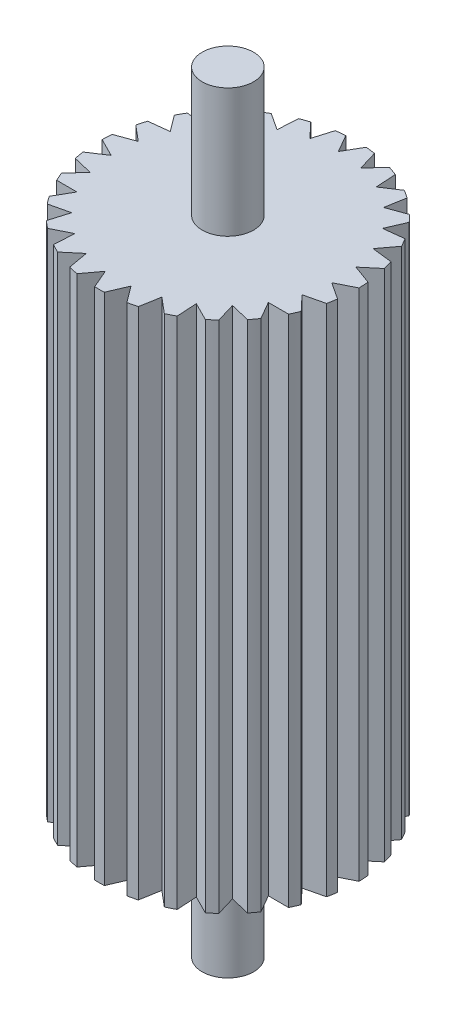
SolidWorks part; units mm, degrees
ref_plane "Front Plane" through (0, 0, 0) normal (0, 0, 1) x (1, 0, 0)
ref_plane "Top Plane" through (0, 0, 0) normal (0, 1, 0) x (1, 0, 0)
ref_plane "Right Plane" through (0, 0, 0) normal (1, 0, 0) x (0, 0, -1)
sketch "Sketch1" plane through (0, 0, 0) normal (0, 1, 0) x (1, 0, 0)
  circle A0 centre (0, 0) radius 12.7
  dimension "D1" = 25.4
extrude "Boss-Extrude2" add sketch "Sketch1" along normal blind 50.8
sketch "Sketch2" plane through (0, 50.8, 0) normal (0, 1, 0) x (1, 0, 0)
  line L0 (2.5188, 10.6276) -> (4.6321, 12.8676)
  line L1 (0, 10.922) -> (1.5398, 13.589)
  line L2 (1.5398, 13.589) -> (-1.5398, 13.589)
  line L3 (-1.5398, 13.589) -> (0, 10.922)
  line L4 (4.6321, 12.8676) -> (1.6356, 13.5778)
  line L5 (1.6356, 13.5778) -> (2.5188, 10.6276)
  line L6 (4.9018, 9.7603) -> (7.4747, 11.4525)
  line L7 (7.4747, 11.4525) -> (4.7227, 12.8346)
  line L8 (4.7227, 12.8346) -> (4.9018, 9.7603)
  line L9 (7.0205, 8.3667) -> (9.9144, 9.42)
  line L10 (9.9144, 9.42) -> (7.5553, 11.3995)
  line L11 (7.5553, 11.3995) -> (7.0205, 8.3667)
  line L12 (8.7608, 6.5222) -> (11.8196, 6.8797)
  line L13 (11.8196, 6.8797) -> (9.9806, 9.3499)
  line L14 (9.9806, 9.3499) -> (8.7608, 6.5222)
  line L15 (10.0288, 4.326) -> (13.0875, 3.9685)
  line L16 (13.0875, 3.9685) -> (11.8678, 6.7962)
  line L17 (11.8678, 6.7962) -> (10.0288, 4.326)
  line L18 (10.7561, 1.8966) -> (13.6499, 0.8433)
  line L19 (13.6499, 0.8433) -> (13.1152, 3.8761)
  line L20 (13.1152, 3.8761) -> (10.7561, 1.8966)
  line L21 (10.9035, -0.6351) -> (13.4765, -2.3273)
  line L22 (13.4765, -2.3273) -> (13.6555, 0.7471)
  line L23 (13.6555, 0.7471) -> (10.9035, -0.6351)
  line L24 (10.4632, -3.1325) -> (12.5765, -5.3725)
  line L25 (12.5765, -5.3725) -> (13.4597, -2.4223)
  line L26 (13.4597, -2.4223) -> (10.4632, -3.1325)
  line L27 (9.4587, -5.461) -> (10.9985, -8.128)
  line L28 (10.9985, -8.128) -> (12.5383, -5.461)
  line L29 (12.5383, -5.461) -> (9.4587, -5.461)
  line L30 (7.9444, -7.4951) -> (8.8276, -10.4453)
  line L31 (8.8276, -10.4453) -> (10.941, -8.2053)
  line L32 (10.941, -8.2053) -> (7.9444, -7.4951)
  line L33 (6.0017, -9.1252) -> (6.1808, -12.1996)
  line L34 (6.1808, -12.1996) -> (8.7538, -10.5073)
  line L35 (8.7538, -10.5073) -> (6.0017, -9.1252)
  line L36 (3.7355, -10.2633) -> (3.2008, -13.2961)
  line L37 (3.2008, -13.2961) -> (6.0946, -12.2428)
  line L38 (6.0946, -12.2428) -> (3.7355, -10.2633)
  line L39 (1.268, -10.8481) -> (0.0482, -13.6759)
  line L40 (0.0482, -13.6759) -> (3.107, -13.3184)
  line L41 (3.107, -13.3184) -> (1.268, -10.8481)
  line L42 (-1.268, -10.8481) -> (-3.107, -13.3184)
  line L43 (-3.107, -13.3184) -> (-0.0482, -13.6759)
  line L44 (-0.0482, -13.6759) -> (-1.268, -10.8481)
  line L45 (-3.7355, -10.2633) -> (-6.0946, -12.2428)
  line L46 (-6.0946, -12.2428) -> (-3.2008, -13.2961)
  line L47 (-3.2008, -13.2961) -> (-3.7355, -10.2633)
  line L48 (-6.0017, -9.1252) -> (-8.7538, -10.5073)
  line L49 (-8.7538, -10.5073) -> (-6.1808, -12.1996)
  line L50 (-6.1808, -12.1996) -> (-6.0017, -9.1252)
  line L51 (-7.9444, -7.4951) -> (-10.941, -8.2053)
  line L52 (-10.941, -8.2053) -> (-8.8276, -10.4453)
  line L53 (-8.8276, -10.4453) -> (-7.9444, -7.4951)
  line L54 (-9.4587, -5.461) -> (-12.5383, -5.461)
  line L55 (-12.5383, -5.461) -> (-10.9985, -8.128)
  line L56 (-10.9985, -8.128) -> (-9.4587, -5.461)
  line L57 (-10.4632, -3.1325) -> (-13.4597, -2.4223)
  line L58 (-13.4597, -2.4223) -> (-12.5765, -5.3725)
  line L59 (-12.5765, -5.3725) -> (-10.4632, -3.1325)
  line L60 (-10.9035, -0.6351) -> (-13.6555, 0.7471)
  line L61 (-13.6555, 0.7471) -> (-13.4765, -2.3273)
  line L62 (-13.4765, -2.3273) -> (-10.9035, -0.6351)
  line L63 (-10.7561, 1.8966) -> (-13.1152, 3.8761)
  line L64 (-13.1152, 3.8761) -> (-13.6499, 0.8433)
  line L65 (-13.6499, 0.8433) -> (-10.7561, 1.8966)
  line L66 (-10.0288, 4.326) -> (-11.8678, 6.7962)
  line L67 (-11.8678, 6.7962) -> (-13.0875, 3.9685)
  line L68 (-13.0875, 3.9685) -> (-10.0288, 4.326)
  line L69 (-8.7608, 6.5222) -> (-9.9806, 9.3499)
  line L70 (-9.9806, 9.3499) -> (-11.8196, 6.8797)
  line L71 (-11.8196, 6.8797) -> (-8.7608, 6.5222)
  line L72 (-7.0205, 8.3667) -> (-7.5553, 11.3995)
  line L73 (-7.5553, 11.3995) -> (-9.9144, 9.42)
  line L74 (-9.9144, 9.42) -> (-7.0205, 8.3667)
  line L75 (-4.9018, 9.7603) -> (-4.7227, 12.8346)
  line L76 (-4.7227, 12.8346) -> (-7.4747, 11.4525)
  line L77 (-7.4747, 11.4525) -> (-4.9018, 9.7603)
  line L78 (-2.5188, 10.6276) -> (-1.6356, 13.5778)
  line L79 (-1.6356, 13.5778) -> (-4.6321, 12.8676)
  line L80 (-4.6321, 12.8676) -> (-2.5188, 10.6276)
  circle A0 centre (0, 12.7) radius 0.889 construction
  circle A1 centre (0, 0) radius 12.7 construction
  point P88 (0, 0)
  dimension "D1" = 1.778
  dimension "D2" = 27
extrude "Cut-Extrude1" cut sketch "Sketch2" against normal blind 50.8
sketch "Sketch3" plane through (0, 0, 0) normal (0, -1, 0) x (-1, 0, 0)
  circle A0 centre (0, 0) radius 2.54
  dimension "D1" = 5.08
extrude "Boss-Extrude3" add sketch "Sketch3" along normal blind 12.7
sketch "Sketch4" plane through (0, 50.8, 0) normal (0, 1, 0) x (1, 0, 0)
  circle A0 centre (0, 0) radius 2.54
  dimension "D1" = 5.08
extrude "Boss-Extrude4" add sketch "Sketch4" along normal blind 12.7
